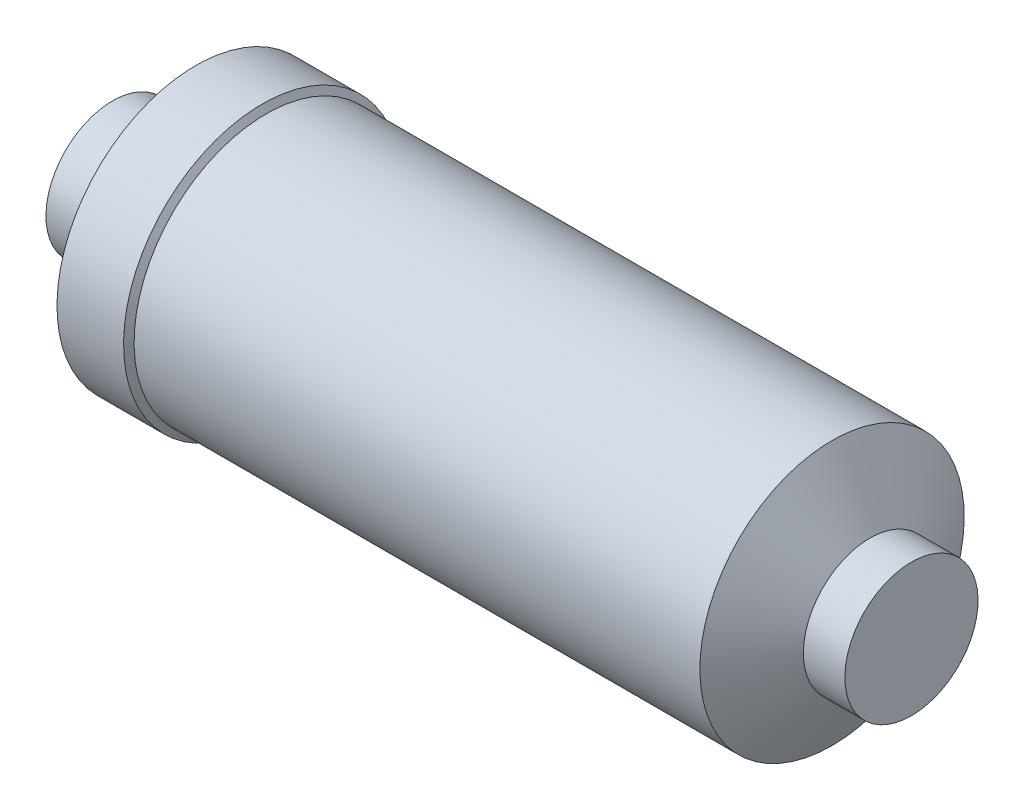
SolidWorks part; units mm, degrees
ref_plane "Front Plane" through (0, 0, 0) normal (0, 0, 1) x (1, 0, 0)
ref_plane "Top Plane" through (0, 0, 0) normal (0, 1, 0) x (1, 0, 0)
ref_plane "Right Plane" through (0, 0, 0) normal (1, 0, 0) x (0, 0, -1)
sketch "Sketch3" plane through (0, 0, 0) normal (0, 0, 1) x (1, 0, 0)
  line L0 (-76.2, 0) -> (76.2, 0) construction
  line L1 (-76.2, 0) -> (-76.2, 12.7)
  line L2 (-76.2, 12.7) -> (-68.2752, 12.7)
  line L3 (-68.2752, 12.7) -> (-60.3196, 26.4795)
  line L4 (-60.3196, 26.4795) -> (-47.6196, 26.4795)
  line L5 (-47.6196, 26.4795) -> (-46.8864, 25.2095)
  line L6 (-46.8864, 25.2095) -> (61.0528, 25.2095)
  line L7 (61.0528, 25.2095) -> (68.2752, 12.7)
  line L8 (68.2752, 12.7) -> (76.2, 12.7)
  line L9 (76.2, 12.7) -> (76.2, 0)
  line L10 (-76.2, 0) -> (76.2, 0)
  point P0 (56.9451, 25.2095)
  point P4 (0, 0)
  point P7 (0, 0)
  point P17 (0, 6.35)
  point P18 (0, 0)
  point P19 (66.4934, 12.7)
  point P20 (-75.2848, 0)
  dimension "D1" = 152.4
  dimension "D2" = 50.419
  dimension "D3" = 12.7
  dimension "D4" = 7.9248
  dimension "D5" = 52.959
  dimension "D6" = 12.7
  dimension "D7" = 60
  dimension "D8" = 120
  dimension "D9" = 60
revolve "Revolve1" add sketch "Sketch3" angle 360 about L0
